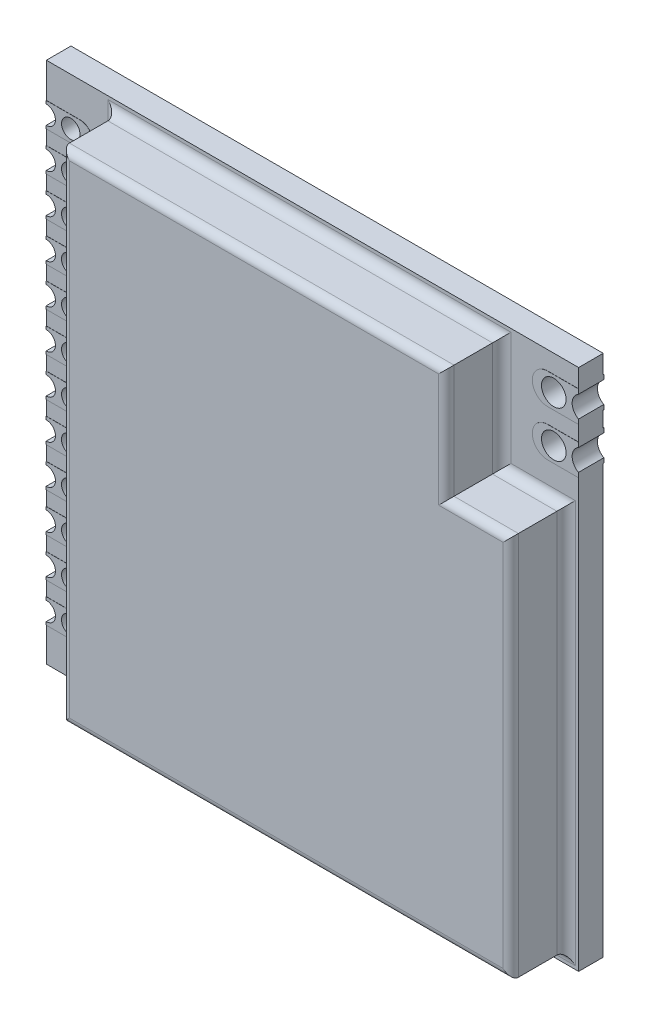
SolidWorks part; units mm, degrees
ref_plane "Front Plane" through (0, 0, 0) normal (0, 0, 1) x (1, 0, 0)
ref_plane "Top Plane" through (0, 0, 0) normal (0, 1, 0) x (1, 0, 0)
ref_plane "Right Plane" through (0, 0, 0) normal (1, 0, 0) x (0, 0, -1)
sketch "Sketch1" plane through (0, 0, 0) normal (0, 0, 1) x (1, 0, 0)
  line L1 (-8.65, 8.5) -> (8.65, 8.5)
  line L2 (-8.65, 8.5) -> (-8.65, -8.5)
  line L3 (-8.65, -8.5) -> (8.65, -8.5)
  line L4 (8.65, 8.5) -> (8.65, -8.5)
  line L5 (-8.65, 8.5) -> (8.65, -8.5) construction
  line L6 (-8.65, -8.5) -> (8.65, 8.5) construction
  point P0 (0, 0)
  dimension "D1" = 17.3
  dimension "D2" = 17
extrude "Boss-Extrude1" add sketch "Sketch1" along normal blind 0.8
sketch "Sketch2" plane through (0, 0, 0.8) normal (0, 0, 1) x (1, 0, 0)
  line L1 (-8.65, 8.5) -> (-8.65, -8.5) construction
  line L2 (8.65, 8.5) -> (-8.65, 8.5) construction
  line L4 (8.65, -8.5) -> (8.65, 8.5) construction
  line L5 (-7.55, 6.57) -> (-8.65, 6.57)
  line L6 (-8.65, 6.57) -> (-8.65, 7.37)
  line L7 (-8.65, 7.37) -> (-7.55, 7.37)
  line L8 (7.65, 7.9) -> (8.65, 7.9)
  line L9 (8.65, 7.9) -> (8.65, 6.9)
  line L10 (8.65, 6.9) -> (7.65, 6.9)
  line L11 (-8.35, 6.97) -> (-8.1527, 6.97) construction
  line L12 (8.2473, 7.4) -> (8.4445, 7.4) construction
  line L13 (-7.55, 5.3) -> (-8.65, 5.3)
  line L14 (-8.65, 6.1) -> (-7.55, 6.1)
  line L15 (-8.65, 5.3) -> (-8.65, 6.1)
  line L16 (-7.55, 4.03) -> (-8.65, 4.03)
  line L17 (-8.65, 4.83) -> (-7.55, 4.83)
  line L18 (-8.65, 4.03) -> (-8.65, 4.83)
  line L19 (-7.55, 2.76) -> (-8.65, 2.76)
  line L20 (-8.65, 3.56) -> (-7.55, 3.56)
  line L21 (-8.65, 2.76) -> (-8.65, 3.56)
  line L22 (-7.55, 1.49) -> (-8.65, 1.49)
  line L23 (-8.65, 2.29) -> (-7.55, 2.29)
  line L24 (-8.65, 1.49) -> (-8.65, 2.29)
  line L25 (-7.55, 0.22) -> (-8.65, 0.22)
  line L26 (-8.65, 1.02) -> (-7.55, 1.02)
  line L27 (-8.65, 0.22) -> (-8.65, 1.02)
  line L28 (-7.55, -1.05) -> (-8.65, -1.05)
  line L29 (-8.65, -0.25) -> (-7.55, -0.25)
  line L30 (-8.65, -1.05) -> (-8.65, -0.25)
  line L31 (-7.55, -2.32) -> (-8.65, -2.32)
  line L32 (-8.65, -1.52) -> (-7.55, -1.52)
  line L33 (-8.65, -2.32) -> (-8.65, -1.52)
  line L34 (-7.55, -3.59) -> (-8.65, -3.59)
  line L35 (-8.65, -2.79) -> (-7.55, -2.79)
  line L36 (-8.65, -3.59) -> (-8.65, -2.79)
  line L37 (-7.55, -4.86) -> (-8.65, -4.86)
  line L38 (-8.65, -4.06) -> (-7.55, -4.06)
  line L39 (-8.65, -4.86) -> (-8.65, -4.06)
  line L40 (-7.55, -6.13) -> (-8.65, -6.13)
  line L41 (-8.65, -5.33) -> (-7.55, -5.33)
  line L42 (-8.65, -6.13) -> (-8.65, -5.33)
  line L43 (-7.55, -7.4) -> (-8.65, -7.4)
  line L44 (-8.65, -6.6) -> (-7.55, -6.6)
  line L45 (-8.65, -7.4) -> (-8.65, -6.6)
  line L46 (7.65, 6.4) -> (8.65, 6.4)
  line L47 (8.65, 5.4) -> (7.65, 5.4)
  line L48 (8.65, 6.4) -> (8.65, 5.4)
  circle A0 centre (-7.8527, 6.97) radius 0.3
  arc A1 (-8.65, 7.27) -> (-8.65, 6.67) centre (-8.65, 6.97) cw
  circle A2 centre (7.8473, 7.4) radius 0.4
  arc A3 (8.65, 7.7495) -> (8.65, 7.0505) centre (8.8445, 7.4) ccw
  arc A4 (-7.55, 7.37) -> (-7.55, 6.57) centre (-7.55, 6.97) cw
  arc A5 (7.65, 7.9) -> (7.65, 6.9) centre (7.65, 7.4) ccw
  arc A6 (-7.55, 6.1) -> (-7.55, 5.3) centre (-7.55, 5.7) cw
  arc A7 (-8.65, 6) -> (-8.65, 5.4) centre (-8.65, 5.7) cw
  circle A8 centre (-7.8527, 5.7) radius 0.3
  arc A9 (-7.55, 4.83) -> (-7.55, 4.03) centre (-7.55, 4.43) cw
  arc A10 (-8.65, 4.73) -> (-8.65, 4.13) centre (-8.65, 4.43) cw
  circle A11 centre (-7.8527, 4.43) radius 0.3
  arc A12 (-7.55, 3.56) -> (-7.55, 2.76) centre (-7.55, 3.16) cw
  arc A13 (-8.65, 3.46) -> (-8.65, 2.86) centre (-8.65, 3.16) cw
  circle A14 centre (-7.8527, 3.16) radius 0.3
  arc A15 (-7.55, 2.29) -> (-7.55, 1.49) centre (-7.55, 1.89) cw
  arc A16 (-8.65, 2.19) -> (-8.65, 1.59) centre (-8.65, 1.89) cw
  circle A17 centre (-7.8527, 1.89) radius 0.3
  arc A18 (-7.55, 1.02) -> (-7.55, 0.22) centre (-7.55, 0.62) cw
  arc A19 (-8.65, 0.92) -> (-8.65, 0.32) centre (-8.65, 0.62) cw
  circle A20 centre (-7.8527, 0.62) radius 0.3
  arc A21 (-7.55, -0.25) -> (-7.55, -1.05) centre (-7.55, -0.65) cw
  arc A22 (-8.65, -0.35) -> (-8.65, -0.95) centre (-8.65, -0.65) cw
  circle A23 centre (-7.8527, -0.65) radius 0.3
  arc A24 (-7.55, -1.52) -> (-7.55, -2.32) centre (-7.55, -1.92) cw
  arc A25 (-8.65, -1.62) -> (-8.65, -2.22) centre (-8.65, -1.92) cw
  circle A26 centre (-7.8527, -1.92) radius 0.3
  arc A27 (-7.55, -2.79) -> (-7.55, -3.59) centre (-7.55, -3.19) cw
  arc A28 (-8.65, -2.89) -> (-8.65, -3.49) centre (-8.65, -3.19) cw
  circle A29 centre (-7.8527, -3.19) radius 0.3
  arc A30 (-7.55, -4.06) -> (-7.55, -4.86) centre (-7.55, -4.46) cw
  arc A31 (-8.65, -4.16) -> (-8.65, -4.76) centre (-8.65, -4.46) cw
  circle A32 centre (-7.8527, -4.46) radius 0.3
  arc A33 (-7.55, -5.33) -> (-7.55, -6.13) centre (-7.55, -5.73) cw
  arc A34 (-8.65, -5.43) -> (-8.65, -6.03) centre (-8.65, -5.73) cw
  circle A35 centre (-7.8527, -5.73) radius 0.3
  arc A36 (-7.55, -6.6) -> (-7.55, -7.4) centre (-7.55, -7) cw
  arc A37 (-8.65, -6.7) -> (-8.65, -7.3) centre (-8.65, -7) cw
  circle A38 centre (-7.8527, -7) radius 0.3
  arc A39 (7.65, 6.4) -> (7.65, 5.4) centre (7.65, 5.9) ccw
  arc A40 (8.65, 6.2495) -> (8.65, 5.5505) centre (8.8445, 5.9) ccw
  circle A41 centre (7.8473, 5.9) radius 0.4
  point P31 (7.15, 7.4)
  point P32 (-7.15, 6.97)
  line M19 (8.65, -8.5) -> (8.65, 8.5)
  line M21 (-8.65, 8.5) -> (-8.65, -8.5)
  dimension "D1" = 0.6
  dimension "D3" = 0.8
  dimension "D2" = 1.53
  dimension "D4" = 15.7
  dimension "D5" = 1.1
  dimension "D6" = 0.8
  dimension "D7" = 1
  dimension "D8" = 1.5
  dimension "D9" = 1.5
  dimension "D10" = 12
  dimension "D11" = 2
extrude "Boss-Extrude2" add sketch "Sketch2" along normal blind 0.005 and the other way offset from surface (0.818 mm away) 0.018 contours A4 L7 A1 L5 A0 M21 | A7 L13 A6 L14 A8 M21 | A10 L16 A9 L17 A11 M21 | A13 L19 A12 L20 A14 M21 | A16 L22 A15 L23 A17 M21 | A19 L25 A18 L26 A20 M21 | A22 L28 A21 L29 A23 M21 | A25 L31 A24 L32 A26 M21 | A28 L34 A27 L35 A29 M21 | A31 L37 A30 L38 A32 M21 | A34 L40 A33 L41 A35 M21 | A37 L43 A36 L44 A38 M21 | A40 L46 A39 L47 A41 M19 | L8 A5 L10 A3 A2 M19 other way up to face at (0, 0, 0)
sketch "Sketch3" plane through (0, 0, 0.805) normal (0, 0, 1) x (1, 0, 0)
  line L0 (-8.65, 0.32) -> (-8.65, 0.22) construction
  line L1 (8.65, 7.7495) -> (8.65, 7.0505)
  line L2 (8.65, 6.2495) -> (8.65, 5.5505)
  line L3 (-8.65, 7.27) -> (-8.65, 6.67)
  line L4 (-8.65, -6.7) -> (-8.65, -7.3)
  line L5 (-8.65, -5.43) -> (-8.65, -6.03)
  line L6 (-8.65, -4.16) -> (-8.65, -4.76)
  line L7 (-8.65, 6) -> (-8.65, 5.4)
  line L8 (-8.65, 4.73) -> (-8.65, 4.13)
  line L9 (-8.65, 3.46) -> (-8.65, 2.86)
  line L10 (-8.65, 2.19) -> (-8.65, 1.59)
  line L11 (-8.65, 0.92) -> (-8.65, 0.32)
  line L12 (-8.65, -0.35) -> (-8.65, -0.95)
  line L13 (-8.65, -1.62) -> (-8.65, -2.22)
  line L14 (-8.65, -2.89) -> (-8.65, -3.49)
  circle A0 centre (-7.8527, 6.97) radius 0.3
  circle A1 centre (-7.8527, 5.7) radius 0.3
  circle A2 centre (-7.8527, 4.43) radius 0.3
  circle A3 centre (-7.8527, 3.16) radius 0.3
  circle A4 centre (-7.8527, 1.89) radius 0.3
  circle A5 centre (-7.8527, 0.62) radius 0.3
  circle A6 centre (-7.8527, -0.65) radius 0.3
  circle A7 centre (-7.8527, -1.92) radius 0.3
  circle A8 centre (-7.8527, -3.19) radius 0.3
  circle A9 centre (-7.8527, -4.46) radius 0.3
  circle A10 centre (-7.8527, -5.73) radius 0.3
  circle A11 centre (-7.8527, -7) radius 0.3
  circle A12 centre (7.8473, 7.4) radius 0.4
  circle A13 centre (7.8473, 5.9) radius 0.4
  arc A14 (-8.65, 7.27) -> (-8.65, 6.67) centre (-8.65, 6.97) cw
  arc A15 (-8.65, 6.67) -> (-8.65, 7.27) centre (-8.65, 6.97) ccw construction
  arc A16 (-8.65, 6) -> (-8.65, 5.4) centre (-8.65, 5.7) cw
  arc A17 (-8.65, 4.73) -> (-8.65, 4.13) centre (-8.65, 4.43) cw
  arc A18 (-8.65, 4.13) -> (-8.65, 4.73) centre (-8.65, 4.43) ccw construction
  arc A19 (-8.65, 3.46) -> (-8.65, 2.86) centre (-8.65, 3.16) cw
  arc A20 (-8.65, 2.19) -> (-8.65, 1.59) centre (-8.65, 1.89) cw
  arc A21 (-8.65, 1.59) -> (-8.65, 2.19) centre (-8.65, 1.89) ccw construction
  arc A22 (-8.65, 0.92) -> (-8.65, 0.32) centre (-8.65, 0.62) cw
  arc A23 (-8.65, 0.32) -> (-8.65, 0.92) centre (-8.65, 0.62) ccw construction
  arc A24 (-8.65, -0.35) -> (-8.65, -0.95) centre (-8.65, -0.65) cw
  arc A25 (-8.65, -0.95) -> (-8.65, -0.35) centre (-8.65, -0.65) ccw construction
  arc A26 (-8.65, -1.62) -> (-8.65, -2.22) centre (-8.65, -1.92) cw
  arc A27 (-8.65, -2.89) -> (-8.65, -3.49) centre (-8.65, -3.19) cw
  arc A28 (-8.65, -4.16) -> (-8.65, -4.76) centre (-8.65, -4.46) cw
  arc A29 (-8.65, -5.43) -> (-8.65, -6.03) centre (-8.65, -5.73) cw
  arc A30 (-8.65, -6.7) -> (-8.65, -7.3) centre (-8.65, -7) cw
  arc A31 (8.65, 6.2495) -> (8.65, 5.5505) centre (8.8445, 5.9) ccw
  arc A32 (8.65, 7.0505) -> (8.65, 7.7495) centre (8.8445, 7.4) cw
extrude "Cut-Extrude1" cut sketch "Sketch3" against normal through all
sketch "Sketch4" plane through (0, 0, 0.8) normal (0, 0, 1) x (1, 0, 0)
  line L0 (6.15, 8.093) -> (6.15, 4.4)
  line L1 (-6.35, 8.093) -> (6.15, 8.093)
  line L2 (-6.35, 8.093) -> (-6.35, -8.093)
  line L3 (-6.35, -8.093) -> (8.243, -8.093)
  line L4 (8.243, 4.4) -> (8.243, -8.093)
  line L5 (-0.1, 8.093) -> (-0.1, 8.5) construction
  line L6 (8.65, 8.5) -> (-8.65, 8.5) construction
  line L7 (6.15, 4.4) -> (8.243, 4.4)
  line L8 (8.65, -8.5) -> (8.65, 5.4) construction
  line L9 (-8.65, -7.4) -> (-8.65, -8.5) construction
  line L10 (8.243, -1.8465) -> (8.65, -1.8465) construction
  line L11 (7.15, 5.9) -> (6.15, 5.9) construction
  line L12 (8.243, 4.4) -> (8.243, 5.4) construction
  line L13 (8.65, 5.4) -> (7.65, 5.4) construction
  arc A0 (7.65, 6.4) -> (7.65, 5.4) centre (7.65, 5.9) ccw construction
  point P0 (-6.35, 0)
  point P13 (-8.65, -7.95)
  dimension "D1" = 2.5
  dimension "D2" = 2.3
extrude "Boss-Extrude3" add sketch "Sketch4" along normal blind 1.8
fillet "Fillet1" radius 0.25 6 edges at (0.9465, -8.093, 2.6) (-6.35, 0, 2.6) (-0.1, 8.093, 2.6) (6.15, 6.2465, 2.6) (7.1965, 4.4, 2.6) (8.243, -1.8465, 2.6)
fillet "Fillet2" radius 0.3 6 edges at (-0.1, 8.093, 0.8) (6.15, 6.2465, 0.8) (7.1965, 4.4, 0.8) (8.243, -1.8465, 0.8) (0.9465, -8.093, 0.8) (-6.35, 0, 0.8)
